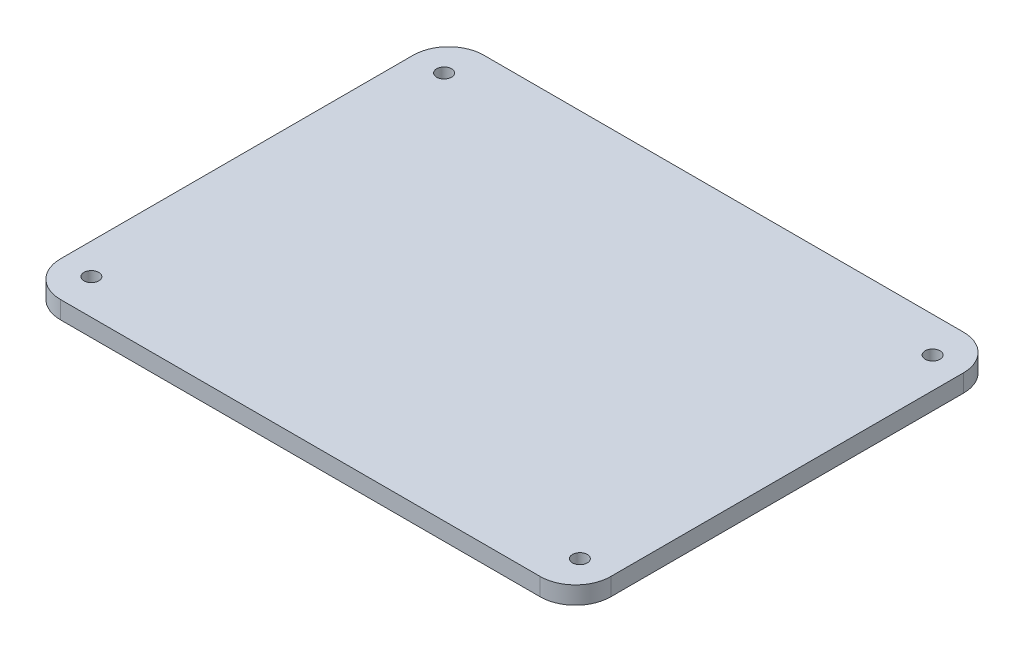
SolidWorks part; units mm, degrees
ref_plane "Front Plane" through (0, 0, 0) normal (0, 0, 1) x (1, 0, 0)
ref_plane "Top Plane" through (0, 0, 0) normal (0, 1, 0) x (1, 0, 0)
ref_plane "Right Plane" through (0, 0, 0) normal (1, 0, 0) x (0, 0, -1)
sketch "Sketch5" plane through (0, 0, 0) normal (0, 1, 0) x (1, 0, 0)
  line L1 (-78, -60) -> (78, -60)
  line L2 (-78, -60) -> (-78, 60)
  line L3 (-78, 60) -> (78, 60)
  line L4 (78, -60) -> (78, 60)
  line L5 (-78, -60) -> (78, 60) construction
  line L6 (-78, 60) -> (78, -60) construction
  point P0 (0, 0)
  dimension "D1" = 156
  dimension "D2" = 120
extrude "Boss-Extrude3" add sketch "Sketch5" along normal blind 5
sketch "Sketch6" plane through (0, 5, 0) normal (0, 1, 0) x (1, 0, 0)
  line L1 (-69.25, -50) -> (69.25, -50)
  line L2 (-69.25, -50) -> (-69.25, 50)
  line L3 (-69.25, 50) -> (69.25, 50)
  line L4 (69.25, -50) -> (69.25, 50)
  line L5 (-69.25, -50) -> (69.25, 50) construction
  line L6 (-69.25, 50) -> (69.25, -50) construction
  circle A0 centre (-69.25, 50) radius 2.1
  circle A1 centre (69.25, 50) radius 2.1
  circle A2 centre (-69.25, -50) radius 2.1
  circle A3 centre (69.25, -50) radius 2.1
  point P0 (0, 0)
  dimension "D3" = 4.2
  dimension "D4" = 4.2
  dimension "D5" = 4.2
  dimension "D6" = 4.2
  dimension "D1" = 138.5
  dimension "D2" = 100
extrude "Cut-Extrude2" cut sketch "Sketch6" against normal through all contours A0 | A2 | A3 | A1
extrude "Cut-Extrude3" cut sketch "Sketch8" against normal blind 10
sketch "Sketch8" [suppressed] plane through (1255.6808, 5, -753.5256) normal (0, 1, 0) x (-0.0007, 0, 1)
  circle A0 centre (704.0212, -1324.4371) radius 3.6442
fillet "Fillet1" radius 10 4 edges at (-78, 2.5, 60) (78, 2.5, 60) (78, 2.5, -60) (-78, 2.5, -60)
